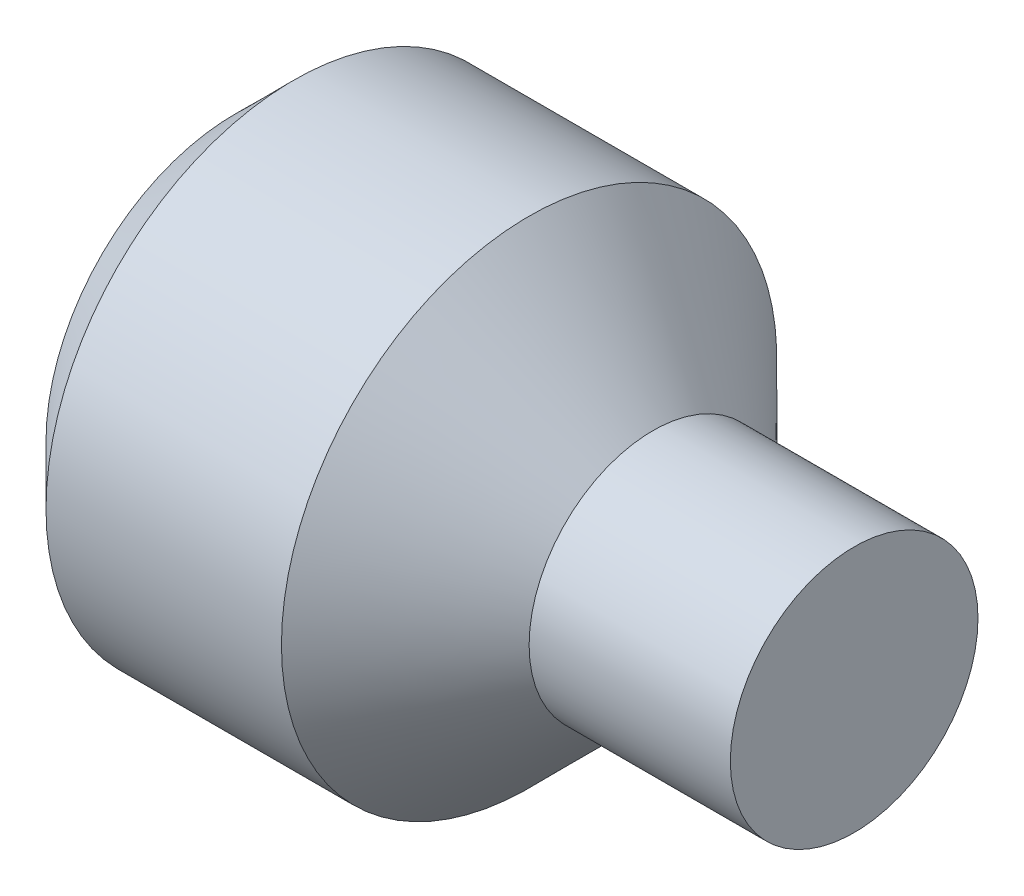
SolidWorks part; units mm, degrees
ref_plane "Front" through (0, 0, 0) normal (0, 0, 1) x (1, 0, 0)
ref_plane "Top" through (0, 0, 0) normal (0, 1, 0) x (1, 0, 0)
ref_plane "Right" through (0, 0, 0) normal (1, 0, 0) x (0, 0, -1)
sketch "Sketch1" plane through (0, 0, 0) normal (0, 0, 1) x (1, 0, 0)
  line L0 (0, 0) -> (2, 0)
  line L1 (2, 0) -> (2, 0.4)
  line L2 (0.95, 0.8) -> (1.35, 0.4)
  line L3 (0.95, 0.8) -> (0.1895, 0.8)
  line L4 (0.1895, 0.8) -> (0, 0.6105)
  line L5 (0, 0.6105) -> (0, 0)
  line L6 (-1.9688, 0) -> (10.951, 0) construction
  line L7 (2, 0.4) -> (1.35, 0.4)
  dimension "l" = 2
  dimension "dp" = 0.8
  dimension "d" = 1.6
  dimension "df" = 1.221
  dimension "D1" = 45
  dimension "D2" = 45
  dimension "z" = 0.65
revolve "Base" add sketch "Sketch1" angle 360 about L6
cosmetic thread "ThreadCosmetic1" [suppressed] parameters "D2"=1.221
sketch "Sketch2" plane through (0, -1.1285, -0.3504) normal (-1, 0, 0) x (0, 0, 1)
  line L1 (0.7545, 1.1285) -> (0.5524, 1.4785)
  line L2 (0.5524, 1.4785) -> (0.1483, 1.4785)
  line L3 (0.1483, 1.4785) -> (-0.0538, 1.1285)
  line L4 (-0.0538, 1.1285) -> (0.1483, 0.7785)
  line L5 (0.1483, 0.7785) -> (0.5524, 0.7785)
  line L6 (0.5524, 0.7785) -> (0.7545, 1.1285)
  circle A0 centre (0.3504, 1.1285) radius 0.35 construction
  dimension "s" = 0.7
  dimension "e" = 0.8083
extrude "HexagonSocket" cut sketch "Sketch2" against normal blind 0.7
sketch "Sketch3" plane through (0, 0, 0) normal (0, 0, 1) x (1, 0, 0)
  line L0 (0.7, 0.35) -> (0.7, 0)
  line L1 (0.7, 0) -> (0.84, 0)
  line L3 (0.84, 0) -> (0.7, 0.35)
  line L4 (-0.331, 0) -> (6.7238, 0) construction
  dimension "h" = 0.14
revolve "Cut-Revolve1" cut sketch "Sketch3" angle 360 about L4
sketch "Sketch4" plane through (0, 0, 0) normal (0, 0, 1) x (1, 0, 0)
  line L0 (0.1895, 0.6359) -> (0.2843, 0.8)
  line L1 (0.2843, 0.8) -> (0.2843, 0.9895)
  line L2 (0.2843, 0.9895) -> (0.0948, 0.9895)
  line L3 (0.0948, 0.9895) -> (0.0948, 0.8)
  line L4 (0.0948, 0.8) -> (0.1895, 0.6359)
  line L5 (0, 0) -> (2.4831, 0) construction
  line L6 (0.1895, 0.8) -> (0.1895, -0.8) construction
  dimension "D1" = 1.6
  dimension "D2" = 0.1895
revolve "Cut-Revolve10" [suppressed] cut sketch "Sketch4" angle 360 about L5
pattern_linear "LPattern10" [suppressed] count 5 spacing 0.2274 along (1, 0, 0)
equation "\"df@Sketch1\" = \"D2@ThreadCosmetic1\""
equation "\"h@Sketch3\" = 0.2 * \"t@HexagonSocket\""
equation "\"D1@Sketch4\" = \"d@Sketch1\""
equation "\"D2@Sketch4\" =  ( \"d@Sketch1\" - \"D2@ThreadCosmetic1\" )  / 2"
equation "\"D3@LPattern10\" = \"D2@Sketch4\" * 1.2"
equation "\"D1@LPattern10\" =  ( \"l@Sketch1\" - \"z@Sketch1\" -  ( \"d@Sketch1\" - \"df@Sketch1\" )  / 2 )  / \"D3@LPattern10\""
